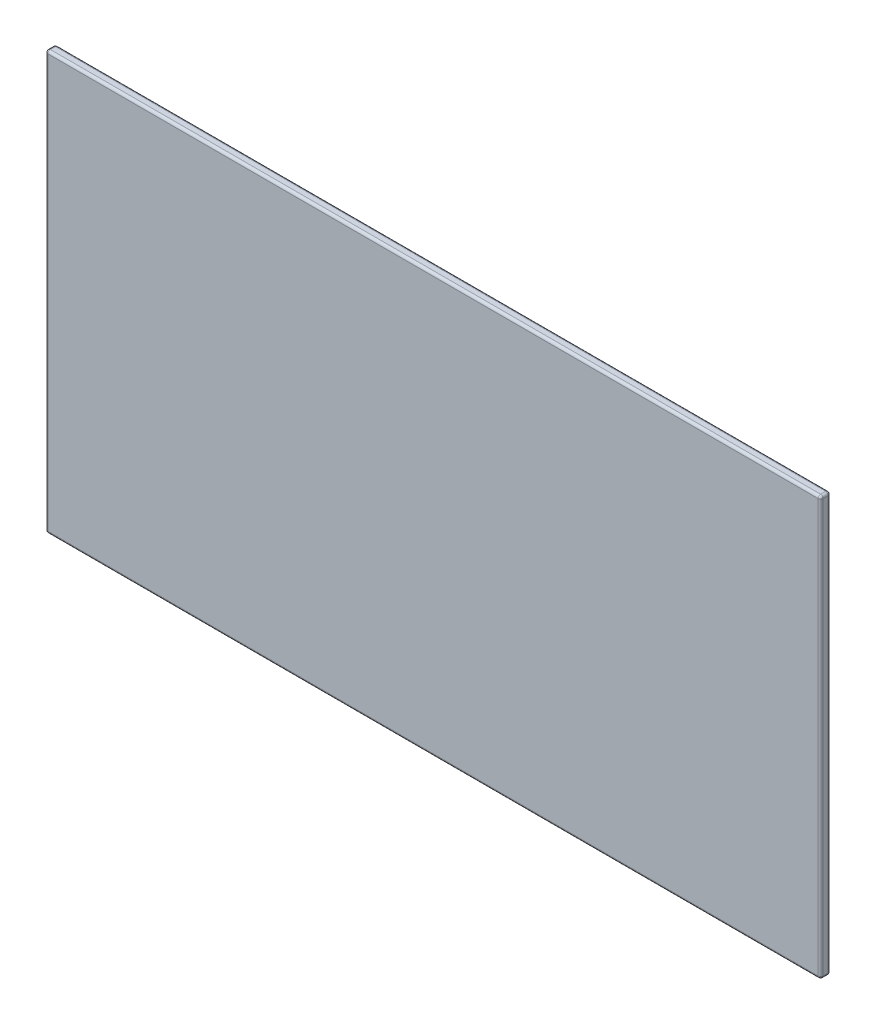
SolidWorks part; units mm, degrees
ref_plane "Front Plane" through (0, 0, 0) normal (0, 0, 1) x (1, 0, 0)
ref_plane "Top Plane" through (0, 0, 0) normal (0, 1, 0) x (1, 0, 0)
ref_plane "Right Plane" through (0, 0, 0) normal (1, 0, 0) x (0, 0, -1)
sketch "Sketch1" plane through (0, 0, 0) normal (0, 0, 1) x (1, 0, 0)
  line L1 (-77.35, -41.75) -> (77.35, -41.75)
  line L2 (-77.35, -41.75) -> (-77.35, 41.75)
  line L3 (-77.35, 41.75) -> (77.35, 41.75)
  line L4 (77.35, -41.75) -> (77.35, 41.75)
  line L5 (-77.35, -41.75) -> (77.35, 41.75) construction
  line L6 (-77.35, 41.75) -> (77.35, -41.75) construction
  point P0 (0, 0)
  dimension "D1" = 154.7
  dimension "D2" = 83.5
extrude "Boss-Extrude1" add sketch "Sketch1" along normal blind 2
fillet "Fillet1" radius 0.5 12 edges at (0, -41.75, 2) (0, -41.75, 0) (-77.35, 0, 2) (-77.35, -41.75, 1) (-77.35, 0, 0) (0, 41.75, 2) (-77.35, 41.75, 1) (0, 41.75, 0) (77.35, -41.75, 1) (77.35, 0, 2) (77.35, 41.75, 1) (77.35, 0, 0)
